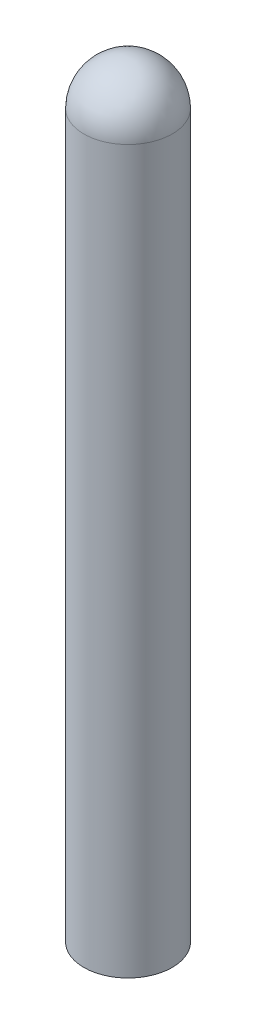
SolidWorks part; units mm, degrees
ref_plane "Front Plane" through (0, 0, 0) normal (0, 0, 1) x (1, 0, 0)
ref_plane "Top Plane" through (0, 0, 0) normal (0, 1, 0) x (1, 0, 0)
ref_plane "Right Plane" through (0, 0, 0) normal (1, 0, 0) x (0, 0, -1)
sketch "Sketch1" plane through (0, 0, 0) normal (0, 1, 0) x (1, 0, 0)
  circle A0 centre (0, 0) radius 2.3812
  dimension "D1" = 4.7625
extrude "Extrude1" add sketch "Sketch1" along normal blind 41.275
fillet "Fillet1" radius 2.3813 1 edges at (0, 41.275, 2.3812)
